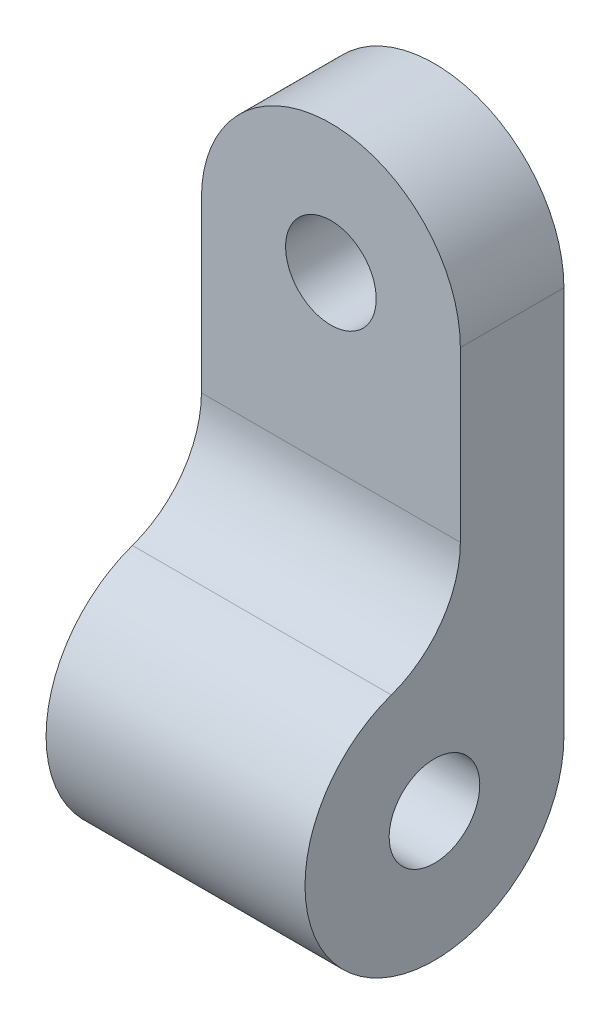
SolidWorks part; units mm, degrees
ref_plane "Plano frontal" through (0, 0, 0) normal (0, 0, 1) x (1, 0, 0)
ref_plane "Plano superior" through (0, 0, 0) normal (0, 1, 0) x (1, 0, 0)
ref_plane "Plano direito" through (0, 0, 0) normal (1, 0, 0) x (0, 0, -1)
sketch "Esboço1" plane through (0, 0, 0) normal (0, 0, 1) x (1, 0, 0)
  line L0 (-5, 0) -> (-5, -20)
  line L3 (-5, -20) -> (5, -20)
  line L6 (5, -20) -> (5, 0)
  arc A0 (5, 0) -> (-5, 0) centre (0, 0) ccw
  circle A1 centre (0, 0) radius 1.75
  point P6 (6.5628, -13.0999)
  point P7 (-5.8779, -12.6285)
  dimension "D1" = 3.5
  dimension "D2" = 10
  dimension "D3" = 20
extrude "Ressalto-extrusão1" add sketch "Esboço1" along normal blind 10
sketch "Esboço2" plane through (-5, 0, 0) normal (-1, 0, 0) x (0, 0, 1)
  line L0 (10, 0) -> (10, -20) construction
  line L1 (0, 0) -> (0, -20) construction
  line L2 (10, -20) -> (0, -20) construction
  line L3 (4, 5) -> (4, -6.5147)
  line L4 (10, 5) -> (0, 5) construction
  line L5 (4, 5) -> (10, 5)
  line L6 (10, 0) -> (10, 5) construction
  line L7 (10, 5) -> (10, -15)
  line L8 (10, -15) -> (10, -20)
  line L9 (10, -20) -> (0, -20)
  line L10 (0, -20) -> (0, -15)
  arc A0 (0, -15) -> (6.6667, -10.286) centre (5, -15) ccw
  circle A1 centre (5, -15) radius 1.75
  arc A2 (4, -6.5147) -> (6.6667, -10.286) centre (8, -6.5147) ccw
  line M2 (0, 0) -> (0, -20)
  line M3 (0, -20) -> (10, -20)
  line M4 (10, -20) -> (10, 0)
  line M5 (10, 0) -> (0, 0)
  dimension "D1" = 3.5
  dimension "D3" = 4
  dimension "D2" = 4
extrude "Corte-extrusão1" cut sketch "Esboço2" against normal blind 10 contours L3 A2 A0 M4 M5 | L7 L5 L3 M5 | A0 L9 M4 | A0 M2 M3 | A1
